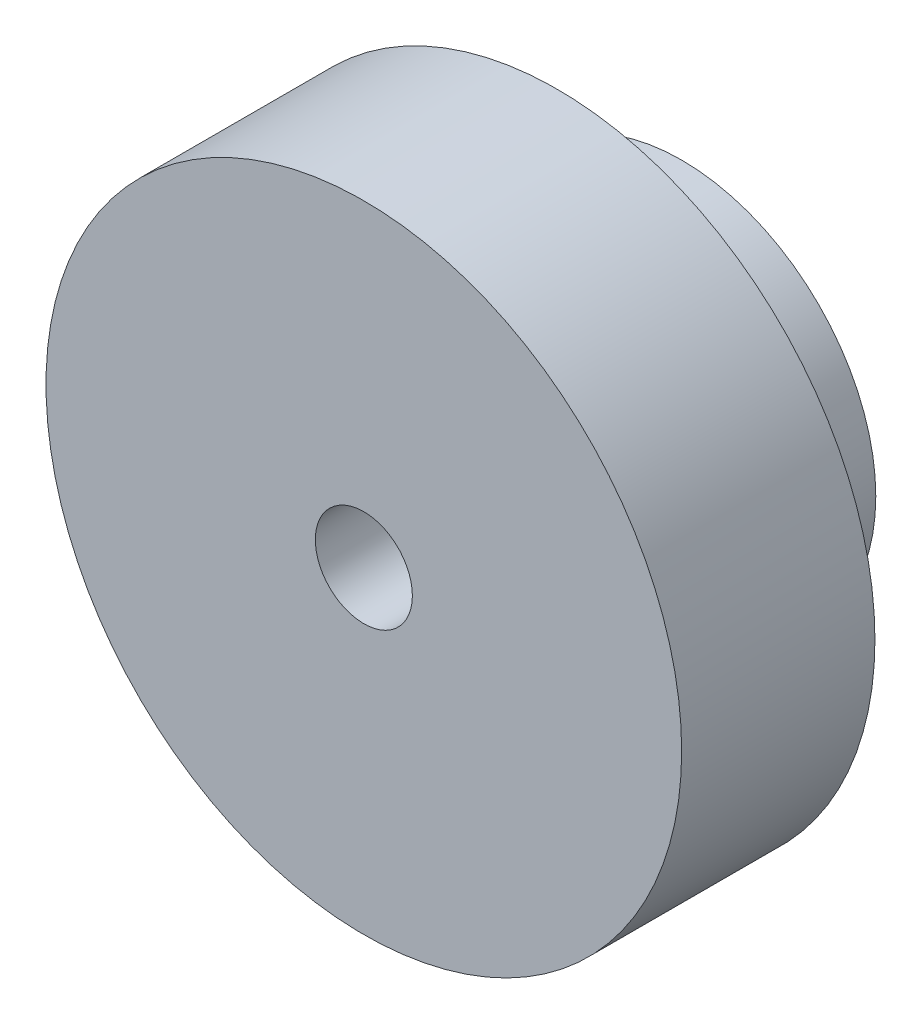
SolidWorks part; units mm, degrees
ref_plane "Front Plane" through (0, 0, 0) normal (0, 0, 1) x (1, 0, 0)
ref_plane "Top Plane" through (0, 0, 0) normal (0, 1, 0) x (1, 0, 0)
ref_plane "Right Plane" through (0, 0, 0) normal (1, 0, 0) x (0, 0, -1)
sketch "Sketch1" plane through (0, 0, 0) normal (0, 0, 1) x (1, 0, 0)
  circle A0 centre (0, 0) radius 9.398
  circle A1 centre (0, 0) radius 1.4351
  dimension "D1" = 18.796
  dimension "D2" = 2.8702
extrude "Boss-Extrude1" add sketch "Sketch1" along normal blind 5.715
sketch "Sketch2" plane through (0, 0, 0) normal (0, 0, -1) x (-1, 0, 0)
  line L0 (3.7644, 3.3591) -> (3.3597, -3.7529)
  line L1 (3.3597, -3.7529) -> (-3.7523, -3.3483)
  line L2 (-3.7523, -3.3483) -> (-3.3476, 3.7637)
  line L3 (-3.3476, 3.7637) -> (3.7644, 3.3591)
  circle A0 centre (0, 0) radius 5.7404
  dimension "D1" = 11.4808
  dimension "D2" = 7.112
  dimension "D3" = 7.112
  dimension "D4" = 3.556
  dimension "D5" = 3.556
extrude "Boss-Extrude2" add sketch "Sketch2" along normal blind 3.683
